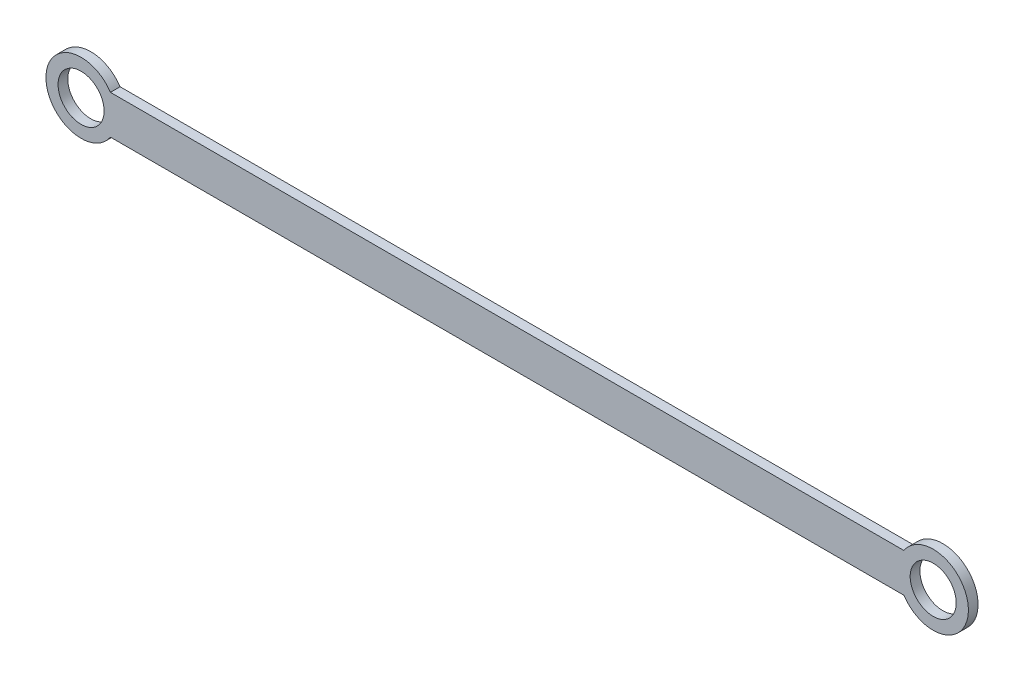
SolidWorks part; units mm, degrees
ref_plane "前视基准面" through (0, 0, 0) normal (0, 0, 1) x (1, 0, 0)
ref_plane "上视基准面" through (0, 0, 0) normal (0, 1, 0) x (1, 0, 0)
ref_plane "右视基准面" through (0, 0, 0) normal (1, 0, 0) x (0, 0, -1)
sketch "草图1" plane through (0, 0, 0) normal (0, 0, 1) x (1, 0, 0)
  line L0 (0, 0) -> (351.4909, 0) construction
  line L1 (9.0139, 3) -> (342.477, 3) construction
  line L2 (9.0139, -3) -> (342.477, -3) construction
  line L3 (12.0934, 8) -> (339.3975, 8)
  line L4 (12.0934, -8) -> (339.3975, -8)
  circle A0 centre (0, 0) radius 9.5
  circle A1 centre (351.4909, 0) radius 9.5
  arc A2 (342.477, 3) -> (342.477, -3) centre (351.4909, 0) cw construction
  arc A3 (9.0139, -3) -> (9.0139, 3) centre (0, 0) cw construction
  arc A4 (12.0934, -8) -> (12.0934, 8) centre (0, 0) cw
  arc A5 (339.3975, 8) -> (339.3975, -8) centre (351.4909, 0) cw
  dimension "D1" = 19
  dimension "D2" = 3
  dimension "D3" = 5
extrude "凸台-拉伸1" add sketch "草图1" along normal blind 4
